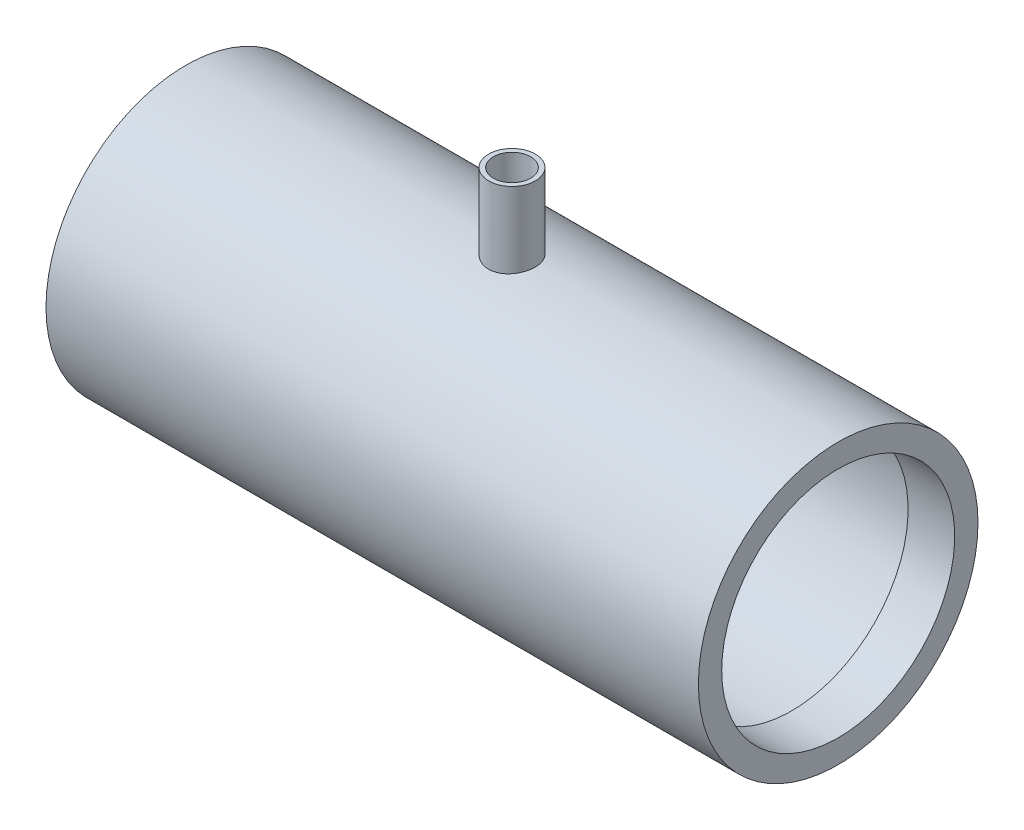
SolidWorks part; units mm, degrees
ref_plane "Front Plane" through (0, 0, 0) normal (0, 0, 1) x (1, 0, 0)
ref_plane "Top Plane" through (0, 0, 0) normal (0, 1, 0) x (1, 0, 0)
ref_plane "Right Plane" through (0, 0, 0) normal (1, 0, 0) x (0, 0, -1)
sketch "Sketch1" plane through (0, 0, 0) normal (1, 0, 0) x (0, 0, -1)
  circle A0 centre (0, 0) radius 15
  circle A1 centre (0, 0) radius 14
  dimension "D1" = 30
extrude "Boss-Extrude1" add sketch "Sketch1" along normal mid plane 60
sketch "Sketch2" plane through (-30, 0, 0) normal (-1, 0, 0) x (0, 0, 1)
  circle A0 centre (0, 0) radius 12.5
  circle A1 centre (0, 0) radius 15
extrude "Boss-Extrude2" add sketch "Sketch2" along normal blind 5
mirror "Mirror1" about plane through (0, 0, 0) normal (1, 0, 0) of "Boss-Extrude2"
sketch "Sketch4" plane through (0, 0, 0) normal (0, 1, 0) x (1, 0, 0)
  circle A0 centre (0, 0) radius 2.5
extrude "Boss-Extrude3" add sketch "Sketch4" along normal blind 23
sketch "Sketch3" plane through (0, 0, 0) normal (0, 1, 0) x (1, 0, 0)
  circle A0 centre (0, 0) radius 2
extrude "Cut-Extrude1" cut sketch "Sketch3" along normal blind 35
sketch "Sketch5" plane through (-30, 0, 0) normal (1, 0, 0) x (0, 0, -1)
  circle A0 centre (0, 0) radius 14 construction
  circle A1 centre (0, 0) radius 14
extrude "Cut-Extrude2" cut sketch "Sketch5" along normal blind 53
